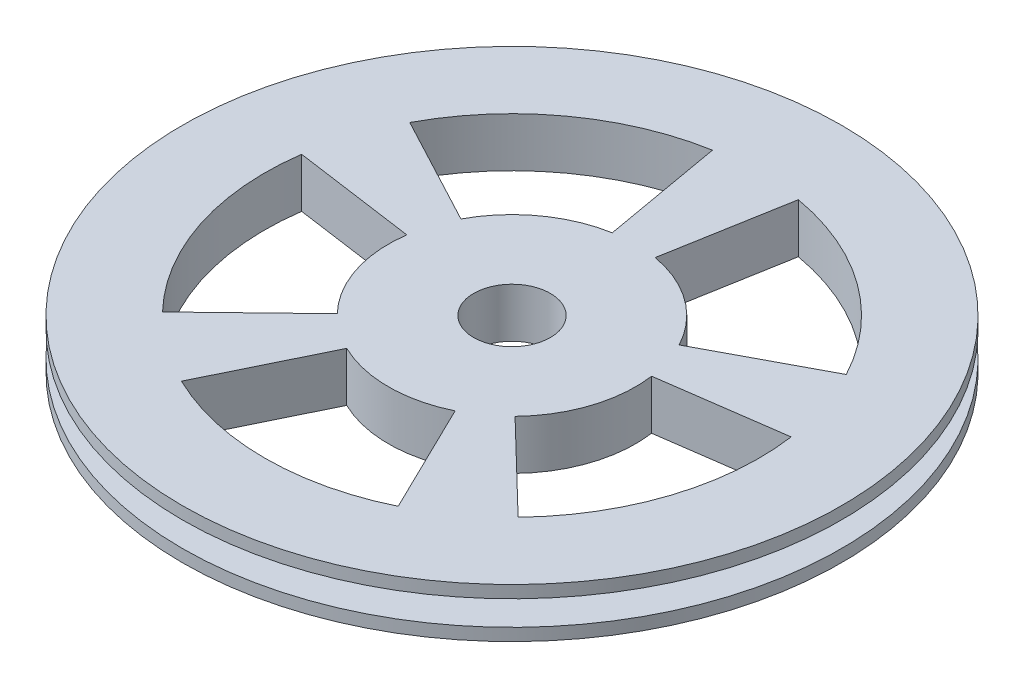
SolidWorks part; units mm, degrees
ref_plane "Front Plane" through (0, 0, 0) normal (0, 0, 1) x (1, 0, 0)
ref_plane "Top Plane" through (0, 0, 0) normal (0, 1, 0) x (1, 0, 0)
ref_plane "Right Plane" through (0, 0, 0) normal (1, 0, 0) x (0, 0, -1)
sketch "Sketch2" plane through (0, 0, 0) normal (0, 1, 0) x (1, 0, 0)
  line L0 (0, 0) -> (-0.4037, 2.2897)
  line L1 (0, 0) -> (0.4037, 2.2897)
  line L2 (5, 28.3564) -> (-5, 28.3564)
  line L3 (0, 0) -> (-49.5144, 0) construction
  line L4 (-3.473, 19.6962) -> (-5, 28.3564)
  line L5 (3.473, 19.6962) -> (5, 28.3564)
  line L6 (-1.3024, 7.3861) -> (-2.6047, 14.7721)
  line L7 (1.3024, 7.3861) -> (2.6047, 14.7721)
  line L8 (6.6221, 3.521) -> (13.2442, 7.0421)
  line L9 (7.427, 1.0438) -> (14.854, 2.0876)
  line L10 (5.395, -5.2099) -> (10.7901, -10.4199)
  line L11 (3.2878, -6.741) -> (6.5756, -13.4819)
  line L12 (-3.2878, -6.741) -> (-6.5756, -13.4819)
  line L13 (-5.395, -5.2099) -> (-10.7901, -10.4199)
  line L14 (-7.427, 1.0438) -> (-14.854, 2.0876)
  line L15 (-6.6221, 3.521) -> (-13.2442, 7.0421)
  circle A0 centre (0, 0) radius 2.325
  circle A1 centre (0, 0) radius 20
  arc A2 (-7.427, 1.0438) -> (-5.395, -5.2099) centre (0, 0) ccw
  arc A3 (-14.854, 2.0876) -> (-10.7901, -10.4199) centre (0, 0) ccw
  arc A4 (-2.6047, 14.7721) -> (-13.2442, 7.0421) centre (0, 0) ccw
  arc A5 (-1.3024, 7.3861) -> (-6.6221, 3.521) centre (0, 0) ccw
  arc A6 (13.2442, 7.0421) -> (2.6047, 14.7721) centre (0, 0) ccw
  arc A7 (6.6221, 3.521) -> (1.3024, 7.3861) centre (0, 0) ccw
  arc A8 (-3.2878, -6.741) -> (3.2878, -6.741) centre (0, 0) ccw
  arc A9 (-6.5756, -13.4819) -> (6.5756, -13.4819) centre (0, 0) ccw
  arc A10 (5.395, -5.2099) -> (7.427, 1.0438) centre (0, 0) ccw
  arc A11 (10.7901, -10.4199) -> (14.854, 2.0876) centre (0, 0) ccw
  point P36 (0, 0)
  dimension "D1" = 4.65
  dimension "D2" = 40
  dimension "D3" = 15
  dimension "D4" = 30
  dimension "D5" = 20
  dimension "D6" = 80
  dimension "D7" = 10
  dimension "D8" = 5
extrude "Boss-Extrude1" add sketch "Sketch2" along normal blind 3 contours L3 A1 A3 L14 A2 A0 A10 L9 A11 L6 A5 L15 A4 L8 A7 L7 A6 | A1 L3 A11 L10 A10 A0 A2 L13 A3 A9 L12 A8 L11
sketch "Sketch3" plane through (0, 0, 0) normal (0, 0, 1) x (1, 0, 0)
  line L1 (20, 3) -> (-20, 3)
  line L2 (-20, 3) -> (-20, 0) construction
  line L3 (-20, 3) -> (-20, 0)
  line L5 (-20, 0) -> (20, 0)
  line L6 (20, 0) -> (20, 3) construction
  line L7 (20, 0) -> (20, 3)
  line L8 (20, 1.5) -> (-20, 1.5) construction
  line L9 (20, 2.25) -> (17, 2.25)
  line L10 (20, 2.25) -> (20, 0.75)
  line L11 (20, 0.75) -> (17, 0.75)
  line L12 (17, 2.25) -> (17, 0.75)
  line L13 (0, 0) -> (0, 19.615) construction
  dimension "D1" = 1.5
  dimension "D2" = 3
revolve "Cut-Revolve1" cut sketch "Sketch3" angle 360 about L13
